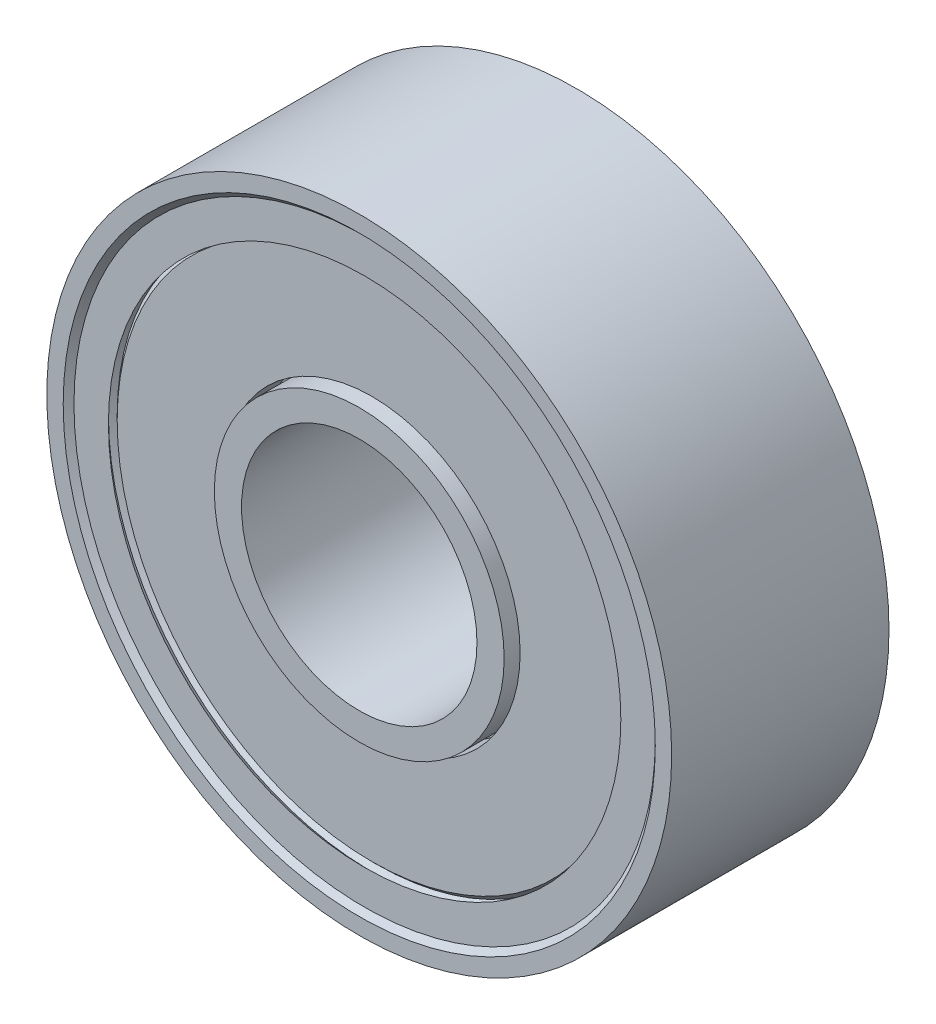
SolidWorks part; units mm, degrees
ref_plane "Front Plane" through (0, 0, 0) normal (0, 0, 1) x (1, 0, 0)
ref_plane "Top Plane" through (0, 0, 0) normal (0, 1, 0) x (1, 0, 0)
ref_plane "Right Plane" through (0, 0, 0) normal (1, 0, 0) x (0, 0, -1)
sketch "Sketch1" plane through (0, 0, 0) normal (0, 0, 1) x (1, 0, 0)
  circle A0 centre (0, 0) radius 6.9
  circle A1 centre (0, 0) radius 2.6
  dimension "D1" = 13.8
  dimension "D2" = 5.2
extrude "Boss-Extrude1" add sketch "Sketch1" along normal blind 4.8
sketch "Sketch2" plane through (0, 0, 0) normal (1, 0, 0) x (0, 0, -1)
  line L0 (-5.048, 6.3) -> (-4.9458, 6.3)
  line L1 (-4.9458, 6.3) -> (-4.9458, 6.6841)
  line L2 (-4.9458, 6.6841) -> (-4.6812, 6.4195)
  line L3 (-4.6812, 6.4195) -> (-4.6812, 5.6584)
  line L4 (-4.6812, 5.6584) -> (-4.5196, 5.8199)
  line L5 (-4.5196, 5.8199) -> (-4.4229, 5.7232)
  line L6 (-4.4229, 5.7232) -> (-4.5196, 5.6265)
  line L7 (-4.5196, 5.6265) -> (-4.5196, 3.2729)
  line L8 (-4.5196, 3.2729) -> (-3.8174, 3.2729)
  line L9 (-3.8174, 3.2729) -> (-3.8174, 3.2)
  line L10 (-3.8174, 3.2) -> (-4.8797, 3.2)
  line L11 (-4.8797, 3.2) -> (-4.8797, 0)
  line L12 (2.64, 0) -> (-2.64, 0) construction
  line L13 (0, 6.9) -> (-4.8, 6.9) construction
  line L14 (-4.8797, 0) -> (-5.8692, 0)
  line L15 (-5.8692, 0) -> (-5.8692, 6.3)
  line L16 (-5.8692, 6.3) -> (-5.048, 6.3)
  line L17 (-2.4, 6.9) -> (-2.4, 5.404) construction
  line L18 (1.0692, 6.3) -> (0.248, 6.3)
  line L19 (1.0692, 0) -> (1.0692, 6.3)
  line L20 (0.0797, 0) -> (1.0692, 0)
  line L21 (0.0797, 3.2) -> (0.0797, 0)
  line L22 (-0.9826, 3.2) -> (0.0797, 3.2)
  line L23 (-0.9826, 3.2729) -> (-0.9826, 3.2)
  line L24 (-0.2804, 3.2729) -> (-0.9826, 3.2729)
  line L25 (-0.2804, 5.6265) -> (-0.2804, 3.2729)
  line L26 (-0.3771, 5.7232) -> (-0.2804, 5.6265)
  line L27 (-0.2804, 5.8199) -> (-0.3771, 5.7232)
  line L28 (-0.1188, 5.6584) -> (-0.2804, 5.8199)
  line L29 (-0.1188, 6.4195) -> (-0.1188, 5.6584)
  line L30 (0.1458, 6.6841) -> (-0.1188, 6.4195)
  line L31 (0.1458, 6.3) -> (0.1458, 6.6841)
  line L32 (0.248, 6.3) -> (0.1458, 6.3)
  point P2 (-2.4, 5.404)
  point P38 (-4.3306, 6.5063)
  point P39 (-4.9458, 6.6841)
  point P40 (-4.5196, 5.8199)
  dimension "D1" = 3.2
  dimension "D2" = 0.6
revolve "Cut-Revolve1" cut sketch "Sketch2" angle 360 about L14
ref_plane "Plane1" through (0, 0, 2.4) normal (0, 0, 1) x (1, 0, 0)
